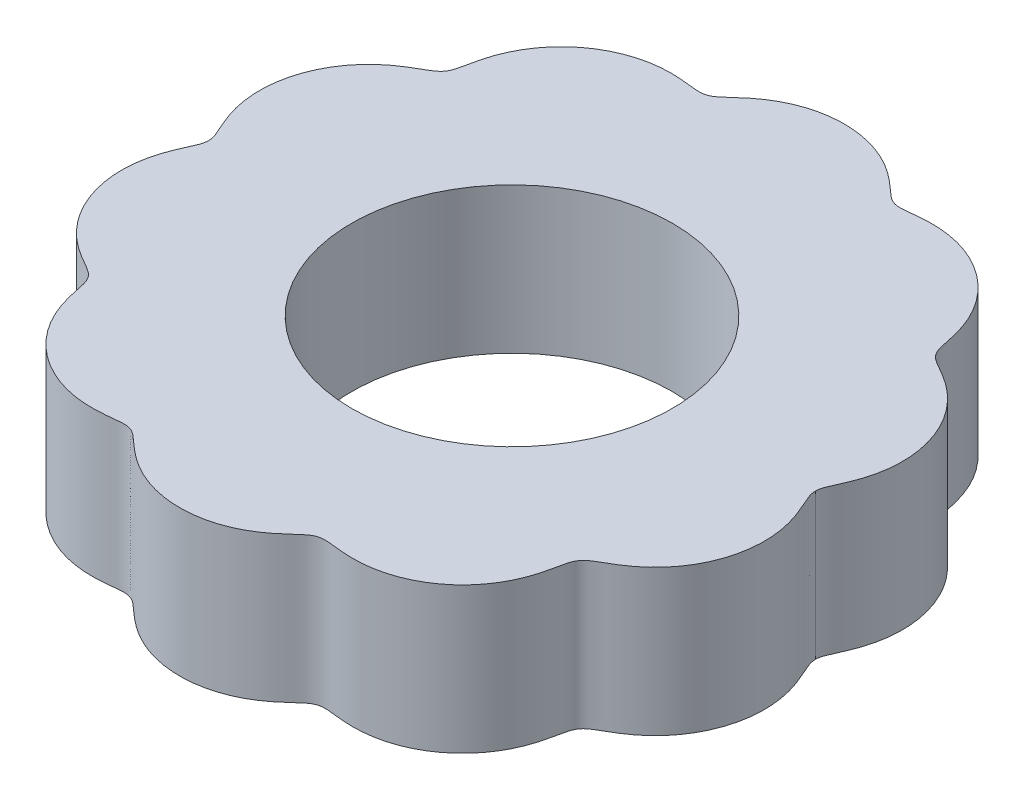
SolidWorks part; units mm, degrees
ref_plane "Front Plane" through (0, 0, 0) normal (0, 0, 1) x (1, 0, 0)
ref_plane "Top Plane" through (0, 0, 0) normal (0, 1, 0) x (1, 0, 0)
ref_plane "Right Plane" through (0, 0, 0) normal (1, 0, 0) x (0, 0, -1)
sketch "Sketch4" plane through (0, 0, 0) normal (0, 1, 0) x (1, 0, 0)
  line L0 (-20.8068, 0) -> (20.8068, 0) construction
  circle A0 centre (0, 0) radius 11
  spline S0 degree 4 poles (21.9253, 6.032) (21.9855, 5.6918) (22.0445, 5.176) (22.0592, 4.4828) (21.9707, 3.6225) (21.8366, 2.9436) (21.6669, 2.3644) (21.4882, 1.8814) (21.3224, 1.4885) (21.201, 1.2181) (21.0959, 0.9876) (21.0048, 0.7793) (20.9295, 0.596) (20.8725, 0.4283) (20.8361, 0.2852) (20.8183, 0.1755) (20.8104, 0.1) (20.8064, 0.0265) (20.8064, -0.027) (20.8105, -0.1012) (20.8185, -0.1774) (20.832, -0.2595) (20.8526, -0.3496) (20.8815, -0.4515) (20.9192, -0.5624) (20.9658, -0.6845) (21.0214, -0.8179) (21.1025, -1.0021) (21.2094, -1.2368) (21.3326, -1.5114) (21.4659, -1.8297) (21.5886, -2.1534) (21.7262, -2.5655) (21.9088, -3.2381) (22.0605, -4.187) (22.063, -5.413) (21.8061, -6.7903) (21.2998, -8.0966) (20.6532, -9.1382) (19.9684, -9.9319) (19.3216, -10.5165) (18.7642, -10.9356) (18.2756, -11.2436) (17.8779, -11.4702) (17.5838, -11.6376) (17.3952, -11.7489) (17.1919, -11.8805) (16.9885, -12.0383) (16.8207, -12.2258) (16.7031, -12.4381) (16.6196, -12.6554) (16.5568, -12.8793) (16.4861, -13.1951) (16.4154, -13.552) (16.3339, -13.9249) (16.2122, -14.3961) (16.0036, -15.0611) (15.6236, -15.9436) (14.9693, -16.9805) (14.0147, -18.0059) (12.8871, -18.8375) (11.6256, -19.4468) (10.4417, -19.7658) (9.3995, -19.8775) (8.6297, -19.8685) (8.1376, -19.8322) (7.7482, -19.7912) (7.4601, -19.7584) (7.1948, -19.7313) (6.9512, -19.7173) (6.7103, -19.7244) (6.4695, -19.7636) (6.2126, -19.8667) (5.9587, -20.0392) (5.7121, -20.2478) (5.4642, -20.4746) (5.2115, -20.705) (4.9489, -20.9339) (4.4767, -21.3192) (3.9026, -21.7161) (3.2113, -22.0909) (2.2369, -22.4717) (1.2206, -22.7289) (0, -22.8424) (-1.2206, -22.7289) (-2.2369, -22.4717) (-3.2113, -22.0909) (-3.9026, -21.7161) (-4.4767, -21.3192) (-4.9489, -20.9339) (-5.2115, -20.705) (-5.4642, -20.4746) (-5.7121, -20.2478) (-5.9587, -20.0392) (-6.2126, -19.8667) (-6.4695, -19.7636) (-6.7103, -19.7244) (-6.9512, -19.7173) (-7.1948, -19.7313) (-7.4601, -19.7584) (-7.7482, -19.7912) (-8.1376, -19.8322) (-8.6297, -19.8685) (-9.3995, -19.8775) (-10.4417, -19.7658) (-11.6256, -19.4468) (-12.8871, -18.8375) (-14.0147, -18.0059) (-14.9693, -16.9805) (-15.6236, -15.9436) (-16.0036, -15.0611) (-16.2122, -14.3961) (-16.3339, -13.9249) (-16.4155, -13.5519) (-16.486, -13.1951) (-16.5673, -12.8334) (-16.6522, -12.5437) (-16.7889, -12.2612) (-16.9886, -12.0383) (-17.1918, -11.8805) (-17.3953, -11.7489) (-17.5838, -11.6376) (-17.8779, -11.4702) (-18.2756, -11.2436) (-18.7642, -10.9356) (-19.3216, -10.5165) (-19.9684, -9.9319) (-20.6532, -9.1382) (-21.2998, -8.0966) (-21.8061, -6.7903) (-22.063, -5.413) (-22.0605, -4.187) (-21.9088, -3.2381) (-21.7262, -2.5655) (-21.5886, -2.1534) (-21.4659, -1.8297) (-21.3326, -1.5114) (-21.2094, -1.2368) (-21.1025, -1.0021) (-21.0214, -0.8179) (-20.9658, -0.6845) (-20.9192, -0.5624) (-20.8815, -0.4515) (-20.8526, -0.3496) (-20.832, -0.2595) (-20.8185, -0.1774) (-20.8105, -0.1012) (-20.8064, -0.027) (-20.8064, 0.0265) (-20.8104, 0.1) (-20.8183, 0.1755) (-20.8314, 0.2568) (-20.8516, 0.3455) (-20.8798, 0.4458) (-20.9165, 0.5548) (-20.962, 0.6748) (-21.0163, 0.8061) (-21.0959, 0.9873) (-21.201, 1.2183) (-21.3224, 1.4884) (-21.4546, 1.8019) (-21.5769, 2.1212) (-21.715, 2.5287) (-21.8996, 3.1951) (-22.0559, 4.1353) (-22.0642, 5.004) (-21.9855, 5.6918) (-21.9253, 6.032) knots 0 0 0 0 0 0.016201 0.024302 0.032402 0.040503 0.048604 0.052571 0.056538 0.060505 0.062489 0.064473 0.067166 0.069859 0.070683 0.071507 0.072331 0.073154 0.073986 0.074818 0.07565 0.076482 0.077853 0.079225 0.080596 0.081968 0.083984 0.086001 0.090033 0.094065 0.098098 0.102181 0.106264 0.11443 0.130761 0.147092 0.163423 0.179754 0.196085 0.204251 0.212416 0.220582 0.228747 0.231314 0.233881 0.236448 0.239015 0.242667 0.245929 0.248129 0.250329 0.253573 0.256817 0.263306 0.267389 0.271471 0.279637 0.295968 0.312299 0.328631 0.344962 0.361293 0.377624 0.38579 0.393955 0.397354 0.400753 0.404152 0.407551 0.409866 0.412181 0.415443 0.418927 0.422719 0.42651 0.430593 0.434676 0.438759 0.442842 0.459172 0.467338 0.475503 0.491834 0.508166 0.524497 0.532662 0.540828 0.557158 0.561241 0.565324 0.569407 0.57349 0.577281 0.581073 0.584557 0.587819 0.590134 0.592449 0.595848 0.599247 0.602646 0.606045 0.61421 0.622376 0.638707 0.655038 0.671369 0.687701 0.704032 0.720363 0.728529 0.732611 0.736694 0.743183 0.746427 0.749671 0.754071 0.757333 0.760985 0.763552 0.766119 0.768686 0.771253 0.779418 0.787584 0.795749 0.803915 0.820246 0.836577 0.852908 0.869239 0.88557 0.893736 0.897819 0.901902 0.905935 0.909967 0.913999 0.916016 0.918032 0.919404 0.920775 0.922147 0.923518 0.92435 0.925182 0.926014 0.926846 0.927669 0.928493 0.929317 0.930141 0.931487 0.932834 0.934181 0.935527 0.937511 0.939495 0.943462 0.947429 0.951396 0.955447 0.959497 0.967598 0.983799 1 1 1 1 1 construction
  spline S1 degree 4 poles (20.8068, 0) (20.8068, -0.0151) (20.8074, -0.0454) (20.8105, -0.1012) (20.8185, -0.1774) (20.832, -0.2595) (20.8526, -0.3496) (20.8815, -0.4515) (20.9192, -0.5624) (20.9658, -0.6845) (21.0214, -0.8179) (21.1025, -1.0021) (21.2094, -1.2368) (21.3326, -1.5114) (21.4659, -1.8297) (21.5886, -2.1534) (21.7262, -2.5655) (21.9088, -3.2381) (22.0605, -4.187) (22.063, -5.413) (21.8061, -6.7903) (21.2998, -8.0966) (20.6532, -9.1382) (19.9684, -9.9319) (19.3216, -10.5165) (18.7642, -10.9356) (18.2756, -11.2436) (17.8779, -11.4702) (17.5838, -11.6376) (17.3952, -11.7489) (17.1919, -11.8805) (16.9885, -12.0383) (16.8207, -12.2258) (16.7031, -12.4381) (16.6196, -12.6554) (16.5568, -12.8793) (16.4861, -13.1951) (16.4154, -13.552) (16.3339, -13.9249) (16.2122, -14.3961) (16.0036, -15.0611) (15.6236, -15.9436) (14.9693, -16.9805) (14.0147, -18.0059) (12.8871, -18.8375) (11.6256, -19.4468) (10.4417, -19.7658) (9.3995, -19.8775) (8.6297, -19.8685) (8.1376, -19.8322) (7.7482, -19.7912) (7.4601, -19.7584) (7.1948, -19.7313) (6.9512, -19.7173) (6.7103, -19.7244) (6.4695, -19.7636) (6.2126, -19.8667) (5.9587, -20.0392) (5.7121, -20.2478) (5.4642, -20.4746) (5.2115, -20.705) (4.9489, -20.9339) (4.4767, -21.3192) (3.9026, -21.7161) (3.2113, -22.0909) (2.2369, -22.4717) (1.2206, -22.7289) (0, -22.8424) (-1.2206, -22.7289) (-2.2369, -22.4717) (-3.2113, -22.0909) (-3.9026, -21.7161) (-4.4767, -21.3192) (-4.9489, -20.9339) (-5.2115, -20.705) (-5.4642, -20.4746) (-5.7121, -20.2478) (-5.9587, -20.0392) (-6.2126, -19.8667) (-6.4695, -19.7636) (-6.7103, -19.7244) (-6.9512, -19.7173) (-7.1948, -19.7313) (-7.4601, -19.7584) (-7.7482, -19.7912) (-8.1376, -19.8322) (-8.6297, -19.8685) (-9.3995, -19.8775) (-10.4417, -19.7658) (-11.6256, -19.4468) (-12.8871, -18.8375) (-14.0147, -18.0059) (-14.9693, -16.9805) (-15.6236, -15.9436) (-16.0036, -15.0611) (-16.2122, -14.3961) (-16.3339, -13.9249) (-16.4155, -13.5519) (-16.486, -13.1951) (-16.5673, -12.8334) (-16.6522, -12.5437) (-16.7889, -12.2612) (-16.9886, -12.0383) (-17.1918, -11.8805) (-17.3953, -11.7489) (-17.5838, -11.6376) (-17.8779, -11.4702) (-18.2756, -11.2436) (-18.7642, -10.9356) (-19.3216, -10.5165) (-19.9684, -9.9319) (-20.6532, -9.1382) (-21.2998, -8.0966) (-21.8061, -6.7903) (-22.063, -5.413) (-22.0605, -4.187) (-21.9088, -3.2381) (-21.7262, -2.5655) (-21.5886, -2.1534) (-21.4659, -1.8297) (-21.3326, -1.5114) (-21.2094, -1.2368) (-21.1025, -1.0021) (-21.0214, -0.8179) (-20.9658, -0.6845) (-20.9192, -0.5624) (-20.8815, -0.4515) (-20.8526, -0.3496) (-20.832, -0.2595) (-20.8185, -0.1774) (-20.8105, -0.1012) (-20.8074, -0.0454) (-20.8068, -0.0151) (-20.8068, 0) knots 0.073154 0.073154 0.073154 0.073154 0.073154 0.073986 0.074818 0.07565 0.076482 0.077853 0.079225 0.080596 0.081968 0.083984 0.086001 0.090033 0.094065 0.098098 0.102181 0.106264 0.11443 0.130761 0.147092 0.163423 0.179754 0.196085 0.204251 0.212416 0.220582 0.228747 0.231314 0.233881 0.236448 0.239015 0.242667 0.245929 0.248129 0.250329 0.253573 0.256817 0.263306 0.267389 0.271471 0.279637 0.295968 0.312299 0.328631 0.344962 0.361293 0.377624 0.38579 0.393955 0.397354 0.400753 0.404152 0.407551 0.409866 0.412181 0.415443 0.418927 0.422719 0.42651 0.430593 0.434676 0.438759 0.442842 0.459172 0.467338 0.475503 0.491834 0.508166 0.524497 0.532662 0.540828 0.557158 0.561241 0.565324 0.569407 0.57349 0.577281 0.581073 0.584557 0.587819 0.590134 0.592449 0.595848 0.599247 0.602646 0.606045 0.61421 0.622376 0.638707 0.655038 0.671369 0.687701 0.704032 0.720363 0.728529 0.732611 0.736694 0.743183 0.746427 0.749671 0.754071 0.757333 0.760985 0.763552 0.766119 0.768686 0.771253 0.779418 0.787584 0.795749 0.803915 0.820246 0.836577 0.852908 0.869239 0.88557 0.893736 0.897819 0.901902 0.905935 0.909967 0.913999 0.916016 0.918032 0.919404 0.920775 0.922147 0.923518 0.92435 0.925182 0.926014 0.926846 0.926846 0.926846 0.926846 0.926846
  spline S2 degree 4 poles (20.8068, 0) (20.8068, 0.0151) (20.8074, 0.0454) (20.8105, 0.1012) (20.8185, 0.1774) (20.832, 0.2595) (20.8526, 0.3496) (20.8815, 0.4515) (20.9192, 0.5624) (20.9658, 0.6845) (21.0214, 0.8179) (21.1025, 1.0021) (21.2094, 1.2368) (21.3326, 1.5114) (21.4659, 1.8297) (21.5886, 2.1534) (21.7262, 2.5655) (21.9088, 3.2381) (22.0605, 4.187) (22.063, 5.413) (21.8061, 6.7903) (21.2998, 8.0966) (20.6532, 9.1382) (19.9684, 9.9319) (19.3216, 10.5165) (18.7642, 10.9356) (18.2756, 11.2436) (17.8779, 11.4702) (17.5838, 11.6376) (17.3952, 11.7489) (17.1919, 11.8805) (16.9885, 12.0383) (16.8207, 12.2258) (16.7031, 12.4381) (16.6196, 12.6554) (16.5568, 12.8793) (16.4861, 13.1951) (16.4154, 13.552) (16.3339, 13.9249) (16.2122, 14.3961) (16.0036, 15.0611) (15.6236, 15.9436) (14.9693, 16.9805) (14.0147, 18.0059) (12.8871, 18.8375) (11.6256, 19.4468) (10.4417, 19.7658) (9.3995, 19.8775) (8.6297, 19.8685) (8.1376, 19.8322) (7.7482, 19.7912) (7.4601, 19.7584) (7.1948, 19.7313) (6.9512, 19.7173) (6.7103, 19.7244) (6.4695, 19.7636) (6.2126, 19.8667) (5.9587, 20.0392) (5.7121, 20.2478) (5.4642, 20.4746) (5.2115, 20.705) (4.9489, 20.9339) (4.4767, 21.3192) (3.9026, 21.7161) (3.2113, 22.0909) (2.2369, 22.4717) (1.2206, 22.7289) (0, 22.8424) (-1.2206, 22.7289) (-2.2369, 22.4717) (-3.2113, 22.0909) (-3.9026, 21.7161) (-4.4767, 21.3192) (-4.9489, 20.9339) (-5.2115, 20.705) (-5.4642, 20.4746) (-5.7121, 20.2478) (-5.9587, 20.0392) (-6.2126, 19.8667) (-6.4695, 19.7636) (-6.7103, 19.7244) (-6.9512, 19.7173) (-7.1948, 19.7313) (-7.4601, 19.7584) (-7.7482, 19.7912) (-8.1376, 19.8322) (-8.6297, 19.8685) (-9.3995, 19.8775) (-10.4417, 19.7658) (-11.6256, 19.4468) (-12.8871, 18.8375) (-14.0147, 18.0059) (-14.9693, 16.9805) (-15.6236, 15.9436) (-16.0036, 15.0611) (-16.2122, 14.3961) (-16.3339, 13.9249) (-16.4155, 13.5519) (-16.486, 13.1951) (-16.5673, 12.8334) (-16.6522, 12.5437) (-16.7889, 12.2612) (-16.9886, 12.0383) (-17.1918, 11.8805) (-17.3953, 11.7489) (-17.5838, 11.6376) (-17.8779, 11.4702) (-18.2756, 11.2436) (-18.7642, 10.9356) (-19.3216, 10.5165) (-19.9684, 9.9319) (-20.6532, 9.1382) (-21.2998, 8.0966) (-21.8061, 6.7903) (-22.063, 5.413) (-22.0605, 4.187) (-21.9088, 3.2381) (-21.7262, 2.5655) (-21.5886, 2.1534) (-21.4659, 1.8297) (-21.3326, 1.5114) (-21.2094, 1.2368) (-21.1025, 1.0021) (-21.0214, 0.8179) (-20.9658, 0.6845) (-20.9192, 0.5624) (-20.8815, 0.4515) (-20.8526, 0.3496) (-20.832, 0.2595) (-20.8185, 0.1774) (-20.8105, 0.1012) (-20.8074, 0.0454) (-20.8068, 0.0151) (-20.8068, 0) knots 0.073154 0.073154 0.073154 0.073154 0.073154 0.073986 0.074818 0.07565 0.076482 0.077853 0.079225 0.080596 0.081968 0.083984 0.086001 0.090033 0.094065 0.098098 0.102181 0.106264 0.11443 0.130761 0.147092 0.163423 0.179754 0.196085 0.204251 0.212416 0.220582 0.228747 0.231314 0.233881 0.236448 0.239015 0.242667 0.245929 0.248129 0.250329 0.253573 0.256817 0.263306 0.267389 0.271471 0.279637 0.295968 0.312299 0.328631 0.344962 0.361293 0.377624 0.38579 0.393955 0.397354 0.400753 0.404152 0.407551 0.409866 0.412181 0.415443 0.418927 0.422719 0.42651 0.430593 0.434676 0.438759 0.442842 0.459172 0.467338 0.475503 0.491834 0.508166 0.524497 0.532662 0.540828 0.557158 0.561241 0.565324 0.569407 0.57349 0.577281 0.581073 0.584557 0.587819 0.590134 0.592449 0.595848 0.599247 0.602646 0.606045 0.61421 0.622376 0.638707 0.655038 0.671369 0.687701 0.704032 0.720363 0.728529 0.732611 0.736694 0.743183 0.746427 0.749671 0.754071 0.757333 0.760985 0.763552 0.766119 0.768686 0.771253 0.779418 0.787584 0.795749 0.803915 0.820246 0.836577 0.852908 0.869239 0.88557 0.893736 0.897819 0.901902 0.905935 0.909967 0.913999 0.916016 0.918032 0.919404 0.920775 0.922147 0.923518 0.92435 0.925182 0.926014 0.926846 0.926846 0.926846 0.926846 0.926846
  dimension "D1" = 22
extrude "Boss-Extrude3" add sketch "Sketch4" along normal blind 10
